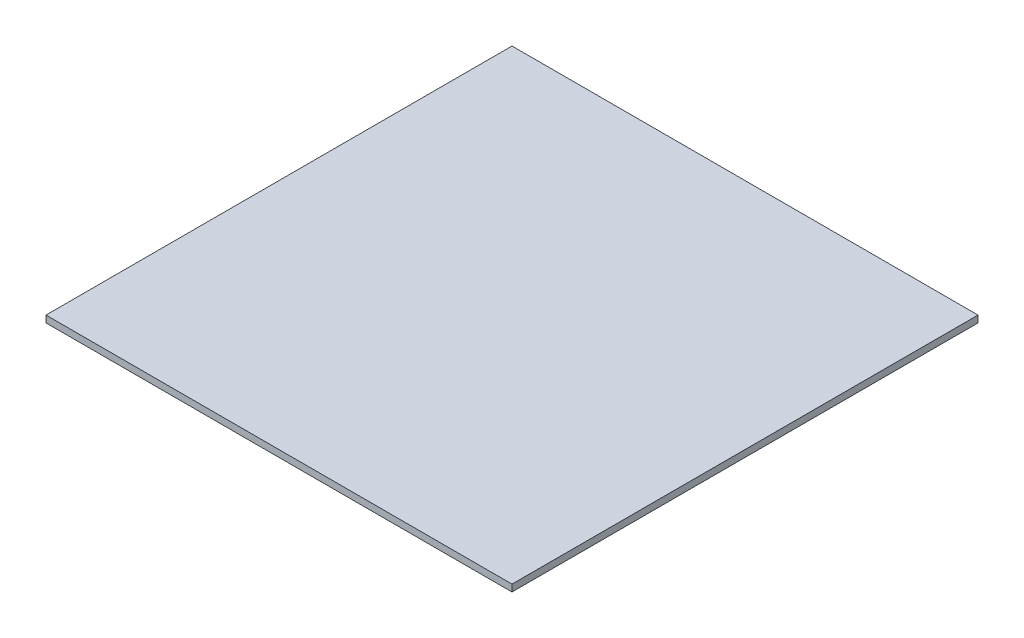
SolidWorks part; units mm, degrees
ref_plane "前视基准面" through (0, 0, 0) normal (0, 0, 1) x (1, 0, 0)
ref_plane "上视基准面" through (0, 0, 0) normal (0, 1, 0) x (1, 0, 0)
ref_plane "右视基准面" through (0, 0, 0) normal (1, 0, 0) x (0, 0, -1)
other "Configuration Table"
sketch "草图1" plane through (0, 0, 0) normal (0, 1, 0) x (1, 0, 0)
  line L1 (-37.5, -37.5) -> (37.5, -37.5)
  line L2 (-37.5, -37.5) -> (-37.5, 37.5)
  line L3 (-37.5, 37.5) -> (37.5, 37.5)
  line L4 (37.5, -37.5) -> (37.5, 37.5)
  line L5 (-37.5, -37.5) -> (37.5, 37.5) construction
  line L6 (-37.5, 37.5) -> (37.5, -37.5) construction
  point P0 (0, 0)
  dimension "D1" = 75
  dimension "D2" = 75
extrude "凸台-拉伸1" add sketch "草图1" along normal blind 1.1
